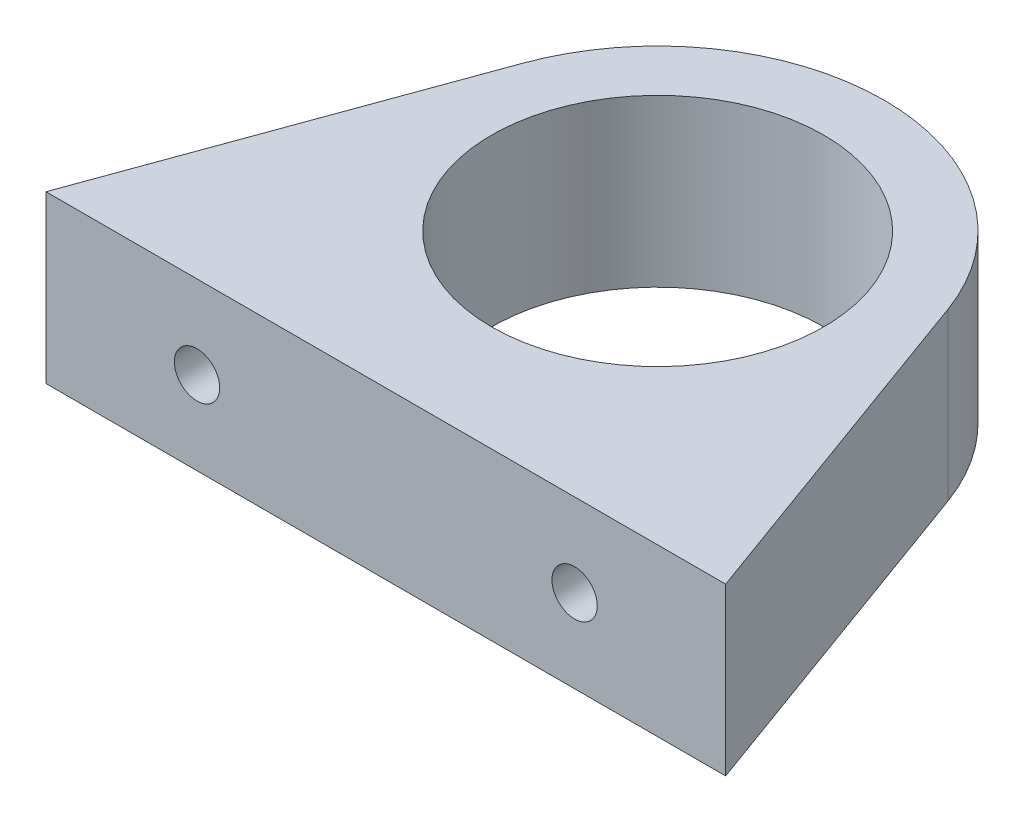
SolidWorks part; units mm, degrees
ref_plane "Front Plane" through (0, 0, 0) normal (0, 0, 1) x (1, 0, 0)
ref_plane "Top Plane" through (0, 0, 0) normal (0, 1, 0) x (1, 0, 0)
ref_plane "Right Plane" through (0, 0, 0) normal (1, 0, 0) x (0, 0, -1)
sketch "Sketch1" plane through (0, 0, 0) normal (0, 1, 0) x (1, 0, 0)
  circle A0 centre (0, 0) radius 11
  circle A1 centre (0, 0) radius 15
  dimension "D1" = 30
  dimension "D2" = 22
extrude "Boss-Extrude1" add sketch "Sketch1" along normal blind 11
sketch "Sketch2" plane through (0, 0, 0) normal (0, 1, 0) x (1, 0, 0)
  line L0 (-22.5, -18) -> (-14.0982, 5.1227)
  line L1 (-22.5, -18) -> (22.5, -18)
  line L2 (0, 31.1512) -> (0, -15) construction
  line L4 (22.5, -18) -> (14.0982, 5.1227)
  line L5 (0, -18) -> (0, -39.1814) construction
  circle A0 centre (0, 0) radius 15 construction
  arc A1 (-14.0982, 5.1227) -> (14.0982, 5.1227) centre (0, 0) ccw
  dimension "D1" = 45
  dimension "D2" = 18
extrude "Boss-Extrude2" add sketch "Sketch2" along normal up to surface (11 mm away) up to face at (0, 11, 15)
sketch "Sketch3" plane through (0, 0, 18) normal (0, 0, 1) x (1, 0, 0)
  line L0 (-22.5, 0) -> (22.5, 0) construction
  line L1 (0, -6.05) -> (0, 6.05) construction
  point P0 (-12.5, 5.5)
  point P1 (0, 0)
  point P7 (12.5, 5.5)
  dimension "D1" = 12.5
  dimension "D2" = 5.5
hole_wizard "Ø3.0 (3) Diameter Hole1" positions "Sketch3" profile "Sketch4" hole size "Ø3.0" standard "ANSI Metric"
sketch "Sketch4" plane through (-12.5, 5.5, 18) normal (1, 0, 0) x (0, -1, 0)
  line L0 (0, 0) -> (0, 10)
  line L1 (0, 10) -> (1.5, 9.0987)
  line L2 (1.5, 9.0987) -> (1.5, 0)
  line L5 (1.5, 0) -> (0, 0)
  line L10 (0, 10) -> (-1.5, 9.0987) construction
  line L11 (0, -6.35) -> (0, 107.95) construction
  dimension "Hole Dia." = 3
  dimension "Hole Depth" = 10
  dimension "Drill Angle" = 118
